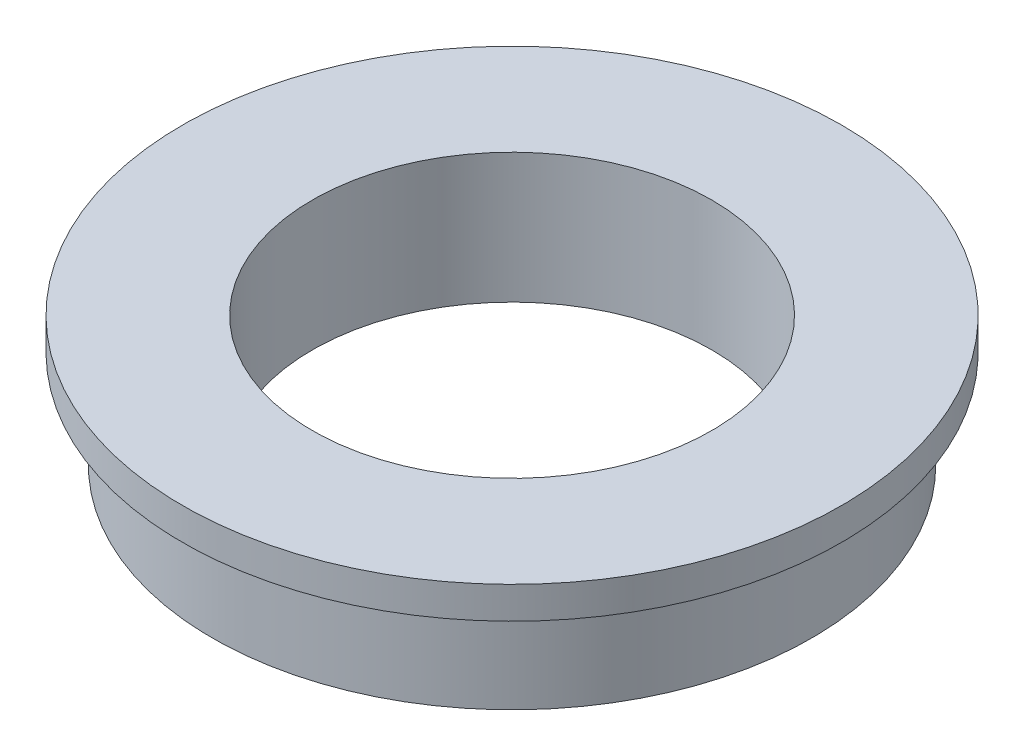
SolidWorks part; units mm, degrees
material "炭素鋼(普通)"
ref_plane "正面" through (0, 0, 0) normal (0, 0, 1) x (1, 0, 0)
ref_plane "平面" through (0, 0, 0) normal (0, 1, 0) x (1, 0, 0)
ref_plane "右側面" through (0, 0, 0) normal (1, 0, 0) x (0, 0, -1)
sketch "ｽｹｯﾁ1" plane through (0, 0, 0) normal (0, 0, 1) x (1, 0, 0)
  line L0 (0, 0) -> (0, 50000) construction
  line L1 (0, 0) -> (50000, 0) construction
  line L2 (5, 0.8) -> (5, -2.45)
  line L3 (5, -2.45) -> (7.5, -2.45)
  line L4 (7.5, -2.45) -> (7.5, 0)
  line L5 (7.5, 0) -> (8.25, 0)
  line L6 (8.25, 0) -> (8.25, 0.8)
  line L7 (8.25, 0.8) -> (5, 0.8)
  dimension "D1" = 0.8
  dimension "D2" = 10
  dimension "D3" = 15
  dimension "D4" = 3.25
  dimension "D5" = 16.5
revolve "回転1" add sketch "ｽｹｯﾁ1" angle 360 about L0
